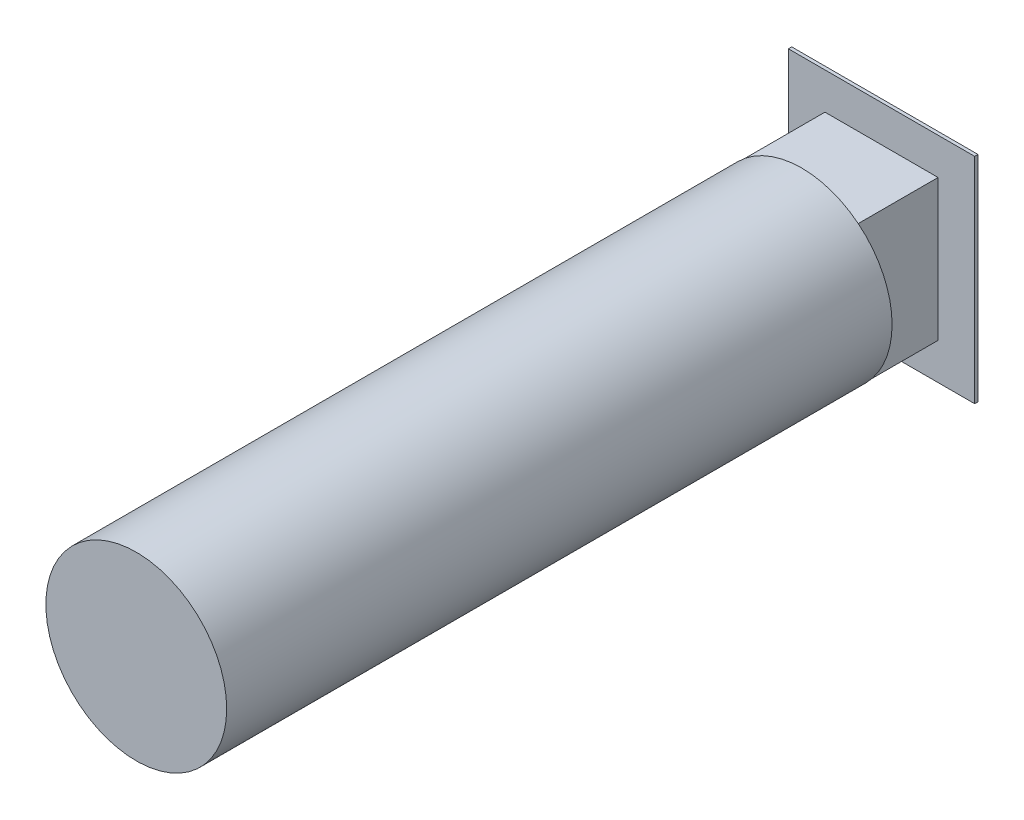
SolidWorks part; units mm, degrees
ref_plane "Alzado" through (0, 0, 0) normal (0, 0, 1) x (1, 0, 0)
ref_plane "Planta" through (0, 0, 0) normal (0, 1, 0) x (1, 0, 0)
ref_plane "Vista lateral" through (0, 0, 0) normal (1, 0, 0) x (0, 0, -1)
sketch "Croquis1" plane through (0, 0, 0) normal (0, 0, 1) x (1, 0, 0)
  line L0 (70, 0) -> (70, -161) construction
  line L1 (0, 0) -> (140, 0)
  line L2 (0, 0) -> (0, -161)
  line L3 (0, -161) -> (140, -161)
  line L4 (140, 0) -> (140, -161)
  line L6 (30, -131) -> (110, -131)
  line L7 (30, -131) -> (30, -30)
  line L8 (30, -30) -> (110, -30)
  line L9 (110, -131) -> (110, -30)
  line L10 (30, -131) -> (110, -30) construction
  line L11 (30, -30) -> (110, -131) construction
  point P8 (70, -80.5)
  dimension "D1" = 140
  dimension "D2" = 161
  dimension "D3" = 30
  dimension "D4" = 30
extrude "Saliente-Extruir1" add sketch "Croquis1" along normal blind 2.5
sketch "Croquis2" plane through (0, 0, 2.5) normal (0, 0, 1) x (1, 0, 0)
  line L0 (27.5, -27.5) -> (27.5, -133.5)
  line L1 (30, -30) -> (110, -30)
  line L2 (30, -30) -> (30, -131)
  line L3 (30, -131) -> (110, -131)
  line L4 (110, -30) -> (110, -131)
  line L5 (27.5, -133.5) -> (112.5, -133.5)
  line L6 (112.5, -27.5) -> (112.5, -133.5)
  line L7 (27.5, -27.5) -> (112.5, -27.5)
  dimension "D1" = 2.5
extrude "Saliente-Extruir2" add sketch "Croquis2" along normal blind 60
sketch "Croquis3" plane through (0, 0, 62.5) normal (0, 0, 1) x (1, 0, 0)
  line L0 (70, -27.5) -> (70, -133.5) construction
  line L1 (112.5, -27.5) -> (27.5, -27.5) construction
  line L2 (27.5, -133.5) -> (112.5, -133.5) construction
  circle A0 centre (70, -80.5) radius 67.9356
extrude "Saliente-Extruir3" add sketch "Croquis3" along normal blind 500
